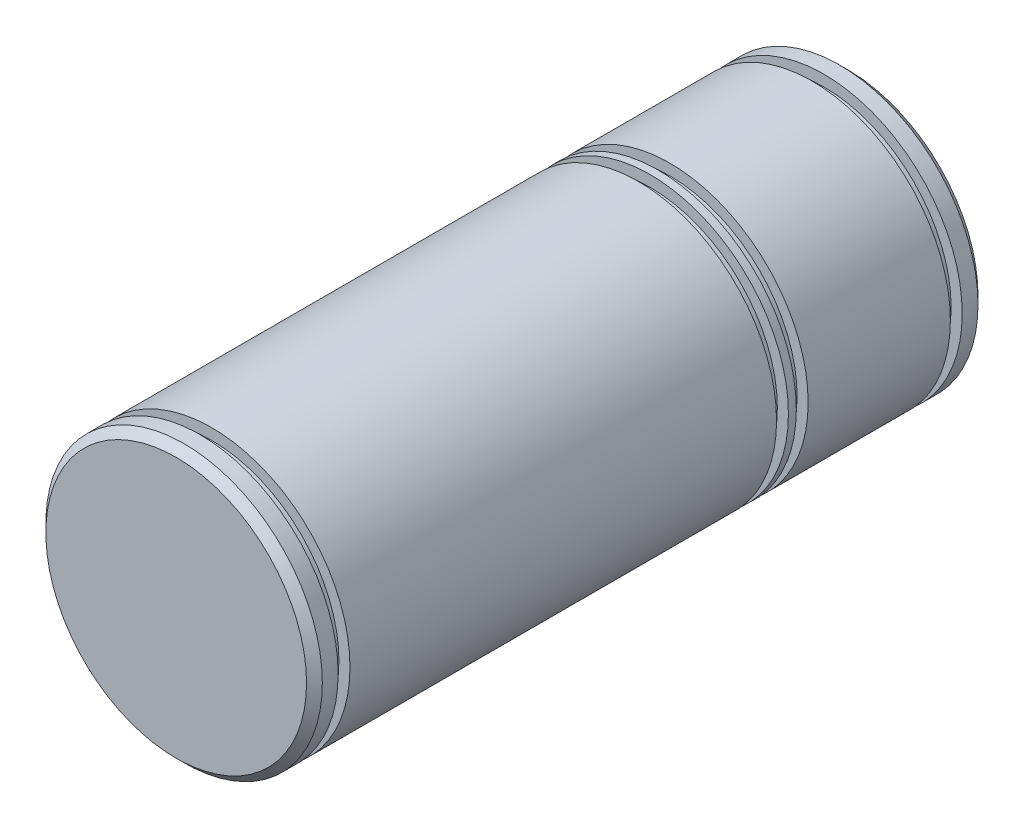
SolidWorks part; units mm, degrees
material "6061-T6 (SS)"
ref_plane "Front Plane" through (0, 0, 0) normal (0, 0, 1) x (1, 0, 0)
ref_plane "Top Plane" through (0, 0, 0) normal (0, 1, 0) x (1, 0, 0)
ref_plane "Right Plane" through (0, 0, 0) normal (1, 0, 0) x (0, 0, -1)
sketch "Sketch1" plane through (0, 0, 0) normal (0, 0, 1) x (1, 0, 0)
  circle A0 centre (0, 0) radius 17.5
  dimension "D1" = 35
extrude "Body" add sketch "Sketch1" along normal blind 85
sketch "Sketch2" plane through (0, 0, 0) normal (1, 0, 0) x (0, 0, -1)
  line L0 (-85, 0) -> (0, 0) construction
  line L1 (-85, 17.5) -> (-85, -17.5) construction
  line L2 (-85, 16.1) -> (0, 16.1) construction
  line L3 (0, -17.5) -> (0, 17.5) construction
  line L4 (0, 17.5) -> (-85, 17.5) construction
  line L7 (-3, 17.5) -> (-4.5, 17.5)
  line L8 (-3, 17.5) -> (-3, 16.1)
  line L9 (-3, 16.1) -> (-4.5, 16.1)
  line L10 (-4.5, 17.5) -> (-4.5, 16.1)
  line L12 (-22.5, 17.5) -> (-24, 17.5)
  line L13 (-22.5, 17.5) -> (-22.5, 16.1)
  line L14 (-22.5, 16.1) -> (-24, 16.1)
  line L15 (-24, 17.5) -> (-24, 16.1)
  line L16 (-25, 17.5) -> (-26.5, 17.5)
  line L17 (-25, 17.5) -> (-25, 16.1)
  line L18 (-25, 16.1) -> (-26.5, 16.1)
  line L19 (-26.5, 17.5) -> (-26.5, 16.1)
  line L20 (-80.5, 17.5) -> (-82, 17.5)
  line L21 (-80.5, 17.5) -> (-80.5, 16.1)
  line L22 (-80.5, 16.1) -> (-82, 16.1)
  line L23 (-82, 17.5) -> (-82, 16.1)
  dimension "D1" = 16.1
  dimension "D2" = 1.5
  dimension "D3" = 1.5
  dimension "D4" = 1.5
  dimension "D5" = 1.5
  dimension "D6" = 4.5
  dimension "D7" = 22.5
  dimension "D8" = 26.5
  dimension "D9" = 80.5
revolve "Ret Ring Grooves" cut sketch "Sketch2" angle 360 about L0
chamfer "Chamfer1" distance 1 angle 45 2 edges at (17.5, 0, 0) (17.5, 0, 85)
equation "\"shaft_diameter\"= 35.0mm"
equation "\"ret_ring_inner_diameter\"= 32.2mm"
equation "\"ret_ring_thickness\"= 1.5mm"
equation "\"ret_ring_1_pos\"= 4.5mm"
equation "\"ret_ring_2_pos\"= 22.5mm"
equation "\"ret_ring_3_pos\"= 26.5mm"
equation "\"ret_ring_4_pos\"= 80.5mm"
equation "\"length\"= 85.0mm"
equation "\"D1@Sketch1\"=\"shaft_diameter\""
equation "\"D1@Body\" = \"length\""
equation "\"D1@Sketch2\"=\"ret_ring_inner_diameter\"/2"
equation "\"D2@Sketch2\"=\"ret_ring_thickness\""
equation "\"D3@Sketch2\"=\"ret_ring_thickness\""
equation "\"D4@Sketch2\"=\"ret_ring_thickness\""
equation "\"D5@Sketch2\"=\"ret_ring_thickness\""
equation "\"D6@Sketch2\"=\"ret_ring_1_pos\""
equation "\"D7@Sketch2\"=\"ret_ring_2_pos\""
equation "\"D8@Sketch2\"=\"ret_ring_3_pos\""
equation "\"D9@Sketch2\"=\"ret_ring_4_pos\""
